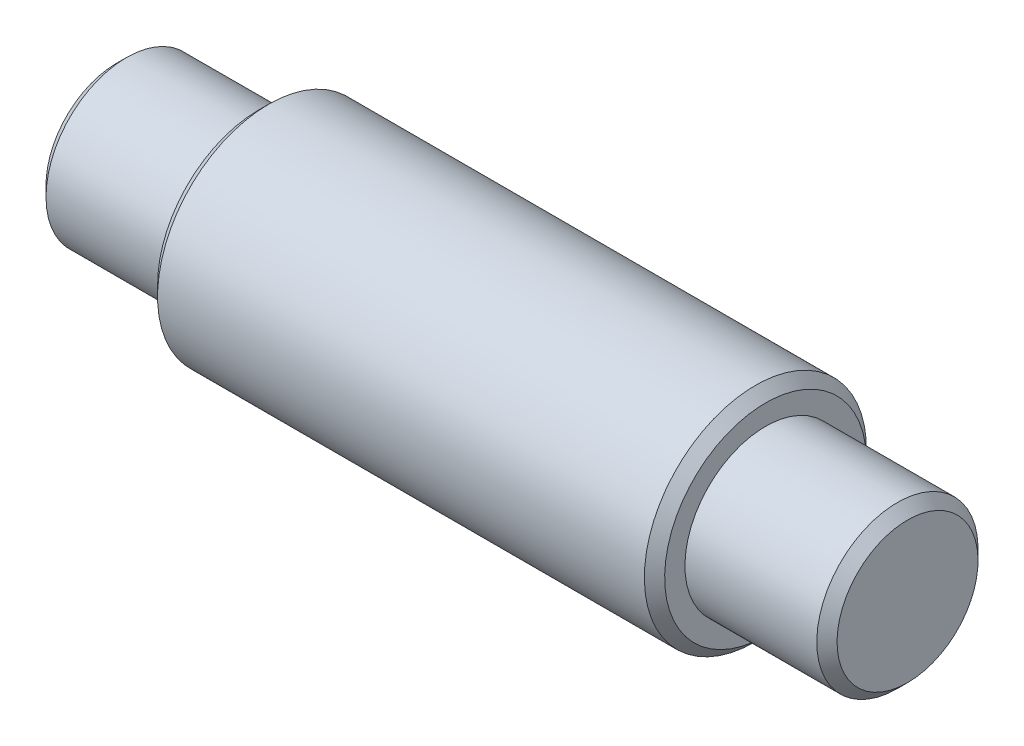
SolidWorks part; units mm, degrees
material "AISI 1020"
ref_plane "Plan de face" through (0, 0, 0) normal (0, 0, 1) x (1, 0, 0)
ref_plane "Plan de dessus" through (0, 0, 0) normal (0, 1, 0) x (1, 0, 0)
ref_plane "Plan de droite" through (0, 0, 0) normal (1, 0, 0) x (0, 0, -1)
sketch "Esquisse1" plane through (0, 0, 0) normal (0, 0, 1) x (1, 0, 0)
  line L0 (-49.1164, 0) -> (49.1164, 0) construction
  line L1 (-39, 0) -> (-39, 7.95)
  line L2 (-39, 7.95) -> (-25, 7.95)
  line L3 (-25, 7.95) -> (-25, 10.95)
  line L4 (-25, 10.95) -> (25, 10.95)
  line L5 (25, 10.95) -> (25, 7.95)
  line L6 (25, 7.95) -> (39, 7.95)
  line L7 (39, 7.95) -> (39, 0)
  line L8 (39, 0) -> (-39, 0)
  point P7 (0, 0)
  point P12 (0, 0)
  dimension "D1" = 78
  dimension "D2" = 50
  dimension "D3" = 15.9
  dimension "D4" = 21.9
revolve "Révolution1" add sketch "Esquisse1" angle 360 about L0
chamfer "Chanfrein1" distance 1 angle 45 4 edges at (39, -7.95, 0) (-39, -7.95, 0) (-25, -10.95, 0) (25, -10.95, 0)
